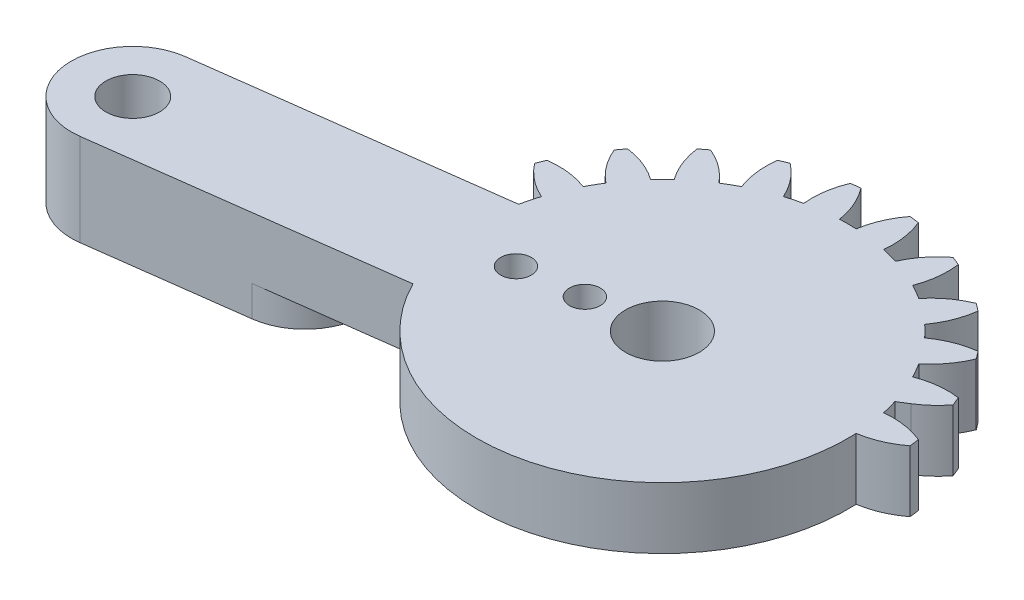
SolidWorks part; units mm, degrees
ref_plane "Front Plane" through (0, 0, 0) normal (0, 0, 1) x (1, 0, 0)
ref_plane "Top Plane" through (0, 0, 0) normal (0, 1, 0) x (1, 0, 0)
ref_plane "Right Plane" through (0, 0, 0) normal (1, 0, 0) x (0, 0, -1)
sketch "Sketch1" plane through (0, 0, 0) normal (0, 1, 0) x (1, 0, 0)
  line L0 (20.6437, 4) -> (2.0816, 4)
  line L1 (2.0816, -4) -> (20.6437, -4)
  arc A0 (2.0816, 4) -> (3.5217, 5.3071) centre (-0.7683, 8.5867) ccw
  arc A1 (3.5217, 5.3071) -> (3.2829, 5.8838) centre (-10.1063, 0) ccw
  arc A2 (3.2829, 5.8838) -> (0.6271, 5.5703) centre (2.5684, 0.5313) ccw
  arc A3 (0.6271, 5.5703) -> (0.0844, 6.5103) centre (-10.1063, 0) ccw
  arc A4 (0.0844, 6.5103) -> (1.6838, 8.6535) centre (-3.3089, 10.711) ccw
  arc A5 (1.6838, 8.6535) -> (1.3038, 9.1487) centre (-10.1063, 0) ccw
  arc A6 (1.3038, 9.1487) -> (-1.1803, 8.1585) centre (1.999, 3.7936) ccw
  arc A7 (-1.1803, 8.1585) -> (-1.9479, 8.926) centre (-10.1063, 0) ccw
  arc A8 (-1.9479, 8.926) -> (-0.9576, 11.4102) centre (-6.3127, 12.1053) ccw
  arc A9 (-0.9576, 11.4102) -> (-1.4528, 11.7901) centre (-10.1063, 0) ccw
  arc A10 (-1.4528, 11.7901) -> (-3.596, 10.1907) centre (0.6046, 6.7975) ccw
  arc A11 (-3.596, 10.1907) -> (-4.5361, 10.7334) centre (-10.1063, 0) ccw
  arc A12 (-4.5361, 10.7334) -> (-4.2225, 13.3892) centre (-9.5751, 12.6747) ccw
  arc A13 (-4.2225, 13.3892) -> (-4.7992, 13.6281) centre (-10.1063, 0) ccw
  arc A14 (-4.7992, 13.6281) -> (-6.4554, 11.5285) centre (-1.5196, 9.3381) ccw
  arc A15 (-6.4554, 11.5285) -> (-7.5039, 11.8094) centre (-10.1063, 0) ccw
  arc A16 (-7.5039, 11.8094) -> (-7.8884, 14.4558) centre (-12.8736, 12.3803) ccw
  arc A17 (-7.8884, 14.4558) -> (-8.5072, 14.5373) centre (-10.1063, 0) ccw
  arc A18 (-8.5072, 14.5373) -> (-9.5636, 12.0806) centre (-4.2291, 11.2423) ccw
  arc A19 (-9.5636, 12.0806) -> (-10.6491, 12.0806) centre (-10.1063, 0) ccw
  arc A20 (-10.6491, 12.0806) -> (-11.7054, 14.5373) centre (-15.9836, 11.2423) ccw
  arc A21 (-11.7054, 14.5373) -> (-12.3243, 14.4558) centre (-10.1063, 0) ccw
  arc A22 (-12.3243, 14.4558) -> (-12.7088, 11.8094) centre (-7.3391, 12.3803) ccw
  arc A23 (-12.7088, 11.8094) -> (-13.7573, 11.5285) centre (-10.1063, 0) ccw
  arc A24 (-13.7573, 11.5285) -> (-15.4135, 13.6281) centre (-18.6931, 9.3381) ccw
  arc A25 (-15.4135, 13.6281) -> (-15.9901, 13.3892) centre (-10.1063, 0) ccw
  arc A26 (-15.9901, 13.3892) -> (-15.6766, 10.7334) centre (-10.6376, 12.6747) ccw
  arc A27 (-15.6766, 10.7334) -> (-16.6166, 10.1907) centre (-10.1063, 0) ccw
  arc A28 (-16.6166, 10.1907) -> (-18.7599, 11.7901) centre (-20.8173, 6.7975) ccw
  arc A29 (-18.7599, 11.7901) -> (-19.255, 11.4102) centre (-10.1063, 0) ccw
  arc A30 (-19.255, 11.4102) -> (-18.2648, 8.926) centre (-13.9, 12.1053) ccw
  arc A31 (-18.2648, 8.926) -> (-19.0324, 8.1585) centre (-10.1063, 0) ccw
  arc A32 (-19.0324, 8.1585) -> (-21.5165, 9.1487) centre (-22.2117, 3.7936) ccw
  arc A33 (-21.5165, 9.1487) -> (-21.8965, 8.6535) centre (-10.1063, 0) ccw
  arc A34 (-21.8965, 8.6535) -> (-20.2971, 6.5103) centre (-16.9038, 10.711) ccw
  arc A35 (-20.2971, 6.5103) -> (-20.8398, 5.5703) centre (-10.1063, 0) ccw
  arc A36 (-20.8398, 5.5703) -> (-23.4956, 5.8838) centre (-22.7811, 0.5313) ccw
  arc A37 (-23.4956, 5.8838) -> (-23.7344, 5.3071) centre (-10.1063, 0) ccw
  arc A38 (-23.7344, 5.3071) -> (-21.6348, 3.6509) centre (-19.4444, 8.5867) ccw
  arc A39 (-21.6348, 3.6509) -> (-21.9157, 2.6025) centre (-10.1063, 0) ccw
  arc A40 (-21.9157, 2.6025) -> (-24.5622, 2.2179) centre (-22.4867, -2.7673) ccw
  arc A41 (-24.5622, 2.2179) -> (-24.6437, 1.5991) centre (-10.1063, 0) ccw
  arc A42 (-24.6437, 1.5991) -> (-22.1869, 0.5427) centre (-21.3486, 5.8773) ccw
  arc A43 (-22.1869, 0.5427) -> (-22.1869, -0.5427) centre (-10.1063, 0) ccw
  arc A44 (-22.1869, -0.5427) -> (-24.6437, -1.5991) centre (-21.3486, -5.8773) ccw
  arc A45 (-24.6437, -1.5991) -> (-24.5622, -2.2179) centre (-10.1063, 0) ccw
  arc A46 (-24.5622, -2.2179) -> (-21.9157, -2.6025) centre (-22.4867, 2.7673) ccw
  arc A47 (-21.9157, -2.6025) -> (-21.6348, -3.6509) centre (-10.1063, 0) ccw
  arc A48 (-21.6348, -3.6509) -> (-23.7344, -5.3071) centre (-19.4444, -8.5867) ccw
  arc A49 (-23.7344, -5.3071) -> (-23.4956, -5.8838) centre (-10.1063, 0) ccw
  arc A50 (-23.4956, -5.8838) -> (-20.8398, -5.5703) centre (-22.7811, -0.5313) ccw
  arc A51 (-20.8398, -5.5703) -> (-20.2971, -6.5103) centre (-10.1063, 0) ccw
  arc A52 (-20.2971, -6.5103) -> (-21.8965, -8.6535) centre (-16.9038, -10.711) ccw
  arc A53 (-21.8965, -8.6535) -> (-21.5165, -9.1487) centre (-10.1063, 0) ccw
  arc A54 (-21.5165, -9.1487) -> (-19.0324, -8.1585) centre (-22.2117, -3.7936) ccw
  arc A55 (-19.0324, -8.1585) -> (-18.2648, -8.926) centre (-10.1063, 0) ccw
  arc A56 (-18.2648, -8.926) -> (-19.255, -11.4102) centre (-13.9, -12.1053) ccw
  arc A57 (-19.255, -11.4102) -> (-18.7599, -11.7901) centre (-10.1063, 0) ccw
  arc A58 (-18.7599, -11.7901) -> (-16.6166, -10.1907) centre (-20.8173, -6.7975) ccw
  arc A59 (-16.6166, -10.1907) -> (-15.6766, -10.7334) centre (-10.1063, 0) ccw
  arc A60 (-15.6766, -10.7334) -> (-15.9901, -13.3892) centre (-10.6376, -12.6747) ccw
  arc A61 (-15.9901, -13.3892) -> (-15.4135, -13.6281) centre (-10.1063, 0) ccw
  arc A62 (-15.4135, -13.6281) -> (-13.7573, -11.5285) centre (-18.6931, -9.3381) ccw
  arc A63 (-13.7573, -11.5285) -> (-12.7088, -11.8094) centre (-10.1063, 0) ccw
  arc A64 (-12.7088, -11.8094) -> (-12.3243, -14.4558) centre (-7.3391, -12.3803) ccw
  arc A65 (-12.3243, -14.4558) -> (-11.7054, -14.5373) centre (-10.1063, 0) ccw
  arc A66 (-11.7054, -14.5373) -> (-10.6491, -12.0806) centre (-15.9836, -11.2423) ccw
  arc A67 (-10.6491, -12.0806) -> (-9.5636, -12.0806) centre (-10.1063, 0) ccw
  arc A68 (-9.5636, -12.0806) -> (-8.5072, -14.5373) centre (-4.2291, -11.2423) ccw
  arc A69 (-8.5072, -14.5373) -> (-7.8884, -14.4558) centre (-10.1063, 0) ccw
  arc A70 (-7.8884, -14.4558) -> (-7.5039, -11.8094) centre (-12.8736, -12.3803) ccw
  arc A71 (-7.5039, -11.8094) -> (-6.4554, -11.5285) centre (-10.1063, 0) ccw
  arc A72 (-6.4554, -11.5285) -> (-4.7992, -13.6281) centre (-1.5196, -9.3381) ccw
  arc A73 (-4.7992, -13.6281) -> (-4.2225, -13.3892) centre (-10.1063, 0) ccw
  arc A74 (-4.2225, -13.3892) -> (-4.5361, -10.7334) centre (-9.5751, -12.6747) ccw
  arc A75 (-4.5361, -10.7334) -> (-3.596, -10.1907) centre (-10.1063, 0) ccw
  arc A76 (-3.596, -10.1907) -> (-1.4528, -11.7901) centre (0.6046, -6.7975) ccw
  arc A77 (-1.4528, -11.7901) -> (-0.9576, -11.4102) centre (-10.1063, 0) ccw
  arc A78 (-0.9576, -11.4102) -> (-1.9479, -8.926) centre (-6.3127, -12.1053) ccw
  arc A79 (-1.9479, -8.926) -> (-1.1803, -8.1585) centre (-10.1063, 0) ccw
  arc A80 (-1.1803, -8.1585) -> (1.3038, -9.1487) centre (1.999, -3.7936) ccw
  arc A81 (1.3038, -9.1487) -> (1.6838, -8.6535) centre (-10.1063, 0) ccw
  arc A82 (1.6838, -8.6535) -> (0.0844, -6.5103) centre (-3.3089, -10.711) ccw
  arc A83 (0.0844, -6.5103) -> (0.6271, -5.5703) centre (-10.1063, 0) ccw
  arc A84 (0.6271, -5.5703) -> (3.2829, -5.8838) centre (2.5684, -0.5313) ccw
  arc A85 (3.2829, -5.8838) -> (3.5217, -5.3071) centre (-10.1063, 0) ccw
  arc A86 (3.5217, -5.3071) -> (2.0816, -4) centre (-0.7683, -8.5867) ccw
  arc A87 (20.6437, -4) -> (20.6437, 4) centre (20.6437, 0) ccw
  circle A88 centre (-10.1063, 0) radius 1.5
  circle A89 centre (20.6437, 0) radius 1.5
  dimension "D1" = 3
  dimension "D2" = 3
extrude "Boss-Extrude1" add sketch "Sketch1" along normal blind 4
sketch "Sketch3" plane through (0, 4, 0) normal (0, 1, 0) x (1, 0, 0)
  line L0 (-10.1063, 0) -> (-40.8563, 0) construction
  line L1 (-10.1063, 0) -> (-40.5933, -4.0137)
  line L2 (-10.6284, 3.9658) -> (-41.1154, -0.0479)
  line L3 (-9.5842, -3.9658) -> (-40.0712, -7.9795)
  line L4 (-10.1063, 0) -> (-4.5096, 13.5117) construction
  line L5 (-10.1063, 0) -> (-8.1974, 14.4999) construction
  circle A0 centre (-10.1063, 0) radius 1.5
  circle A1 centre (20.6437, 0) radius 1.5 construction
  circle A2 centre (20.6437, 0) radius 1.5
  circle A3 centre (-40.5933, -4.0137) radius 1.75
  circle A4 centre (-40.5933, -4.0137) radius 4
  circle A5 centre (-10.1063, 0) radius 4
  arc A6 (-4.2225, 13.3892) -> (-4.7992, 13.6281) centre (-10.1063, 0) ccw construction
  arc A7 (-7.8884, 14.4558) -> (-8.5072, 14.5373) centre (-10.1063, 0) ccw construction
  dimension "D2" = 3
  dimension "D5" = 3.5
  dimension "D6" = 8
  dimension "D7" = 8
  dimension "D1" = 30.75
  dimension "D4" = 7.5
extrude "Boss-Extrude2" add sketch "Sketch3" against normal blind 4
sketch "Sketch4" plane through (0, 4, 0) normal (0, 1, 0) x (1, 0, 0)
  line L0 (20.6437, 4) -> (2.0816, 4) construction
  line L1 (2.0816, -4) -> (20.6437, -4) construction
  line L2 (20.6437, 4) -> (2.0816, 4)
  line L3 (2.0816, -4) -> (20.6437, -4)
  line L4 (2.0816, 4) -> (1.4381, 3.6001)
  line L5 (-21.6245, -5.5509) -> (-20.8986, -5.4553)
  line L6 (-10.1063, 0) -> (0.0844, 6.5103) construction
  line L7 (-10.1063, 0) -> (1.9742, 0.5427) construction
  line L8 (-24.5755, 2.1296) -> (-41.1154, -0.0479)
  line L9 (-40.0712, -7.9795) -> (-23.5312, -5.8019)
  line L10 (2.0816, -4) -> (20.6437, -4)
  line L11 (20.6437, 4) -> (2.0816, 4)
  line L12 (-21.9429, 2.4762) -> (-41.1154, -0.0479)
  line L13 (-40.0712, -7.9795) -> (-21.6245, -5.5509)
  line L14 (2.0816, -4) -> (20.6437, -4)
  line L15 (20.6437, 4) -> (2.0816, 4)
  circle A0 centre (-10.1063, 0) radius 12.0927
  arc A1 (3.2829, 5.8838) -> (0.6271, 5.5703) centre (2.5684, 0.5313) ccw construction
  arc A2 (3.5217, 5.3071) -> (3.2829, 5.8838) centre (-10.1063, 0) ccw construction
  arc A3 (2.0816, 4) -> (3.5217, 5.3071) centre (-0.7683, 8.5867) ccw construction
  arc A4 (20.6437, -4) -> (20.6437, 4) centre (20.6437, 0) ccw construction
  arc A5 (3.5217, -5.3071) -> (2.0816, -4) centre (-0.7683, -8.5867) ccw construction
  arc A6 (3.2829, -5.8838) -> (3.5217, -5.3071) centre (-10.1063, 0) ccw construction
  arc A7 (0.6271, -5.5703) -> (3.2829, -5.8838) centre (2.5684, -0.5313) ccw construction
  arc A8 (3.2829, 5.8838) -> (0.6271, 5.5703) centre (2.5684, 0.5313) ccw
  arc A9 (3.5217, 5.3071) -> (3.2829, 5.8838) centre (-10.1063, 0) ccw
  arc A10 (2.0816, 4) -> (3.5217, 5.3071) centre (-0.7683, 8.5867) ccw
  arc A11 (20.6437, -4) -> (20.6437, 4) centre (20.6437, 0) ccw
  arc A12 (3.5217, -5.3071) -> (2.0816, -4) centre (-0.7683, -8.5867) ccw
  arc A13 (3.2829, -5.8838) -> (3.5217, -5.3071) centre (-10.1063, 0) ccw
  arc A14 (0.6271, -5.5703) -> (3.2829, -5.8838) centre (2.5684, -0.5313) ccw
  arc A15 (1.9742, 0.5427) -> (4.431, 1.5991) centre (1.1359, 5.8773) ccw
  arc A16 (4.3495, 2.2179) -> (1.7031, 2.6025) centre (2.274, -2.7673) ccw
  arc A17 (4.431, 1.5991) -> (4.3495, 2.2179) centre (-10.1063, 0) ccw
  arc A95 (-21.6348, 3.6509) -> (-21.9157, 2.6025) centre (-10.1063, 0) ccw
  arc A96 (-41.1154, -0.0479) -> (-40.0712, -7.9795) centre (-40.5933, -4.0137) ccw
  arc A97 (-20.2971, -6.5103) -> (-21.8965, -8.6535) centre (-16.9038, -10.711) ccw
  arc A98 (-21.8965, -8.6535) -> (-21.5165, -9.1487) centre (-10.1063, 0) ccw
  arc A99 (-21.5165, -9.1487) -> (-19.0324, -8.1585) centre (-22.2117, -3.7936) ccw
  arc A100 (-19.0324, -8.1585) -> (-18.2648, -8.926) centre (-10.1063, 0) ccw
  arc A101 (-18.2648, -8.926) -> (-19.255, -11.4102) centre (-13.9, -12.1053) ccw
  arc A102 (-19.255, -11.4102) -> (-18.7599, -11.7901) centre (-10.1063, 0) ccw
  arc A103 (-18.7599, -11.7901) -> (-16.6166, -10.1907) centre (-20.8173, -6.7975) ccw
  arc A104 (-16.6166, -10.1907) -> (-15.6766, -10.7334) centre (-10.1063, 0) ccw
  arc A105 (-15.6766, -10.7334) -> (-15.9901, -13.3892) centre (-10.6376, -12.6747) ccw
  arc A106 (-15.9901, -13.3892) -> (-15.4135, -13.6281) centre (-10.1063, 0) ccw
  arc A107 (-15.4135, -13.6281) -> (-13.7573, -11.5285) centre (-18.6931, -9.3381) ccw
  arc A108 (-13.7573, -11.5285) -> (-12.7088, -11.8094) centre (-10.1063, 0) ccw
  arc A109 (-12.7088, -11.8094) -> (-12.3243, -14.4558) centre (-7.3391, -12.3803) ccw
  arc A110 (-12.3243, -14.4558) -> (-11.7054, -14.5373) centre (-10.1063, 0) ccw
  arc A111 (-11.7054, -14.5373) -> (-10.6491, -12.0806) centre (-15.9836, -11.2423) ccw
  arc A112 (-10.6491, -12.0806) -> (-9.5636, -12.0806) centre (-10.1063, 0) ccw
  arc A113 (-9.5636, -12.0806) -> (-8.5072, -14.5373) centre (-4.2291, -11.2423) ccw
  arc A114 (-8.5072, -14.5373) -> (-7.8884, -14.4558) centre (-10.1063, 0) ccw
  arc A115 (-7.8884, -14.4558) -> (-7.5039, -11.8094) centre (-12.8736, -12.3803) ccw
  arc A116 (-7.5039, -11.8094) -> (-6.4554, -11.5285) centre (-10.1063, 0) ccw
  arc A117 (-6.4554, -11.5285) -> (-4.7992, -13.6281) centre (-1.5196, -9.3381) ccw
  arc A118 (-4.7992, -13.6281) -> (-4.2225, -13.3892) centre (-10.1063, 0) ccw
  arc A119 (-4.2225, -13.3892) -> (-4.5361, -10.7334) centre (-9.5751, -12.6747) ccw
  arc A120 (-4.5361, -10.7334) -> (-3.596, -10.1907) centre (-10.1063, 0) ccw
  arc A121 (-3.596, -10.1907) -> (-1.4528, -11.7901) centre (0.6046, -6.7975) ccw
  arc A122 (-1.4528, -11.7901) -> (-0.9576, -11.4102) centre (-10.1063, 0) ccw
  arc A123 (-0.9576, -11.4102) -> (-1.9479, -8.926) centre (-6.3127, -12.1053) ccw
  arc A124 (-1.9479, -8.926) -> (-1.1803, -8.1585) centre (-10.1063, 0) ccw
  arc A125 (-1.1803, -8.1585) -> (1.3038, -9.1487) centre (1.999, -3.7936) ccw
  arc A126 (1.3038, -9.1487) -> (1.6838, -8.6535) centre (-10.1063, 0) ccw
  arc A127 (1.6838, -8.6535) -> (0.0844, -6.5103) centre (-3.3089, -10.711) ccw
  arc A128 (0.0844, -6.5103) -> (0.6271, -5.5703) centre (-10.1063, 0) ccw
  arc A129 (0.6271, -5.5703) -> (3.2829, -5.8838) centre (2.5684, -0.5313) ccw
  arc A130 (3.2829, -5.8838) -> (3.5217, -5.3071) centre (-10.1063, 0) ccw
  arc A131 (3.5217, -5.3071) -> (2.0816, -4) centre (-0.7683, -8.5867) ccw
  arc A132 (20.6437, -4) -> (20.6437, 4) centre (20.6437, 0) ccw
  arc A133 (2.0816, 4) -> (3.5217, 5.3071) centre (-0.7683, 8.5867) ccw
  arc A134 (3.5217, 5.3071) -> (3.2829, 5.8838) centre (-10.1063, 0) ccw
  arc A135 (3.2829, 5.8838) -> (0.6271, 5.5703) centre (2.5684, 0.5313) ccw
  arc A136 (0.6271, 5.5703) -> (0.0844, 6.5103) centre (-10.1063, 0) ccw
  arc A137 (0.0844, 6.5103) -> (1.6838, 8.6535) centre (-3.3089, 10.711) ccw
  arc A138 (1.6838, 8.6535) -> (1.3038, 9.1487) centre (-10.1063, 0) ccw
  arc A139 (1.3038, 9.1487) -> (-1.1803, 8.1585) centre (1.999, 3.7936) ccw
  arc A140 (-1.1803, 8.1585) -> (-1.9479, 8.926) centre (-10.1063, 0) ccw
  arc A141 (-1.9479, 8.926) -> (-0.9576, 11.4102) centre (-6.3127, 12.1053) ccw
  arc A142 (-0.9576, 11.4102) -> (-1.4528, 11.7901) centre (-10.1063, 0) ccw
  arc A143 (-1.4528, 11.7901) -> (-3.596, 10.1907) centre (0.6046, 6.7975) ccw
  arc A144 (-3.596, 10.1907) -> (-4.5361, 10.7334) centre (-10.1063, 0) ccw
  arc A145 (-4.5361, 10.7334) -> (-4.2225, 13.3892) centre (-9.5751, 12.6747) ccw
  arc A146 (-4.2225, 13.3892) -> (-4.7992, 13.6281) centre (-10.1063, 0) ccw
  arc A147 (-4.7992, 13.6281) -> (-6.4554, 11.5285) centre (-1.5196, 9.3381) ccw
  arc A148 (-6.4554, 11.5285) -> (-7.5039, 11.8094) centre (-10.1063, 0) ccw
  arc A149 (-7.5039, 11.8094) -> (-7.8884, 14.4558) centre (-12.8736, 12.3803) ccw
  arc A150 (-7.8884, 14.4558) -> (-8.5072, 14.5373) centre (-10.1063, 0) ccw
  arc A151 (-8.5072, 14.5373) -> (-9.5636, 12.0806) centre (-4.2291, 11.2423) ccw
  arc A152 (-9.5636, 12.0806) -> (-10.6491, 12.0806) centre (-10.1063, 0) ccw
  arc A153 (-10.6491, 12.0806) -> (-11.7054, 14.5373) centre (-15.9836, 11.2423) ccw
  arc A154 (-11.7054, 14.5373) -> (-12.3243, 14.4558) centre (-10.1063, 0) ccw
  arc A155 (-12.3243, 14.4558) -> (-12.7088, 11.8094) centre (-7.3391, 12.3803) ccw
  arc A156 (-12.7088, 11.8094) -> (-13.7573, 11.5285) centre (-10.1063, 0) ccw
  arc A157 (-13.7573, 11.5285) -> (-15.4135, 13.6281) centre (-18.6931, 9.3381) ccw
  arc A158 (-15.4135, 13.6281) -> (-15.9901, 13.3892) centre (-10.1063, 0) ccw
  arc A159 (-15.9901, 13.3892) -> (-15.6766, 10.7334) centre (-10.6376, 12.6747) ccw
  arc A160 (-15.6766, 10.7334) -> (-16.6166, 10.1907) centre (-10.1063, 0) ccw
  arc A161 (-16.6166, 10.1907) -> (-18.7599, 11.7901) centre (-20.8173, 6.7975) ccw
  arc A162 (-18.7599, 11.7901) -> (-19.255, 11.4102) centre (-10.1063, 0) ccw
  arc A163 (-19.255, 11.4102) -> (-18.2648, 8.926) centre (-13.9, 12.1053) ccw
  arc A164 (-18.2648, 8.926) -> (-19.0324, 8.1585) centre (-10.1063, 0) ccw
  arc A165 (-19.0324, 8.1585) -> (-21.5165, 9.1487) centre (-22.2117, 3.7936) ccw
  arc A166 (-21.5165, 9.1487) -> (-21.8965, 8.6535) centre (-10.1063, 0) ccw
  arc A167 (-21.8965, 8.6535) -> (-20.2971, 6.5103) centre (-16.9038, 10.711) ccw
  arc A168 (-20.2971, 6.5103) -> (-20.8398, 5.5703) centre (-10.1063, 0) ccw
  arc A169 (-20.8398, 5.5703) -> (-23.4956, 5.8838) centre (-22.7811, 0.5313) ccw
  arc A170 (-23.4956, 5.8838) -> (-23.7344, 5.3071) centre (-10.1063, 0) ccw
  arc A171 (-23.7344, 5.3071) -> (-21.6348, 3.6509) centre (-19.4444, 8.5867) ccw
  arc A172 (-21.6348, 3.6509) -> (-21.9157, 2.6025) centre (-10.1063, 0) ccw
  arc A175 (-23.4956, -5.8838) -> (-20.8398, -5.5703) centre (-22.7811, -0.5313) ccw
  arc A176 (-41.1154, -0.0479) -> (-40.0712, -7.9795) centre (-40.5933, -4.0137) ccw
  arc A177 (-20.2971, -6.5103) -> (-21.8965, -8.6535) centre (-16.9038, -10.711) ccw
  arc A178 (-21.8965, -8.6535) -> (-21.5165, -9.1487) centre (-10.1063, 0) ccw
  arc A179 (-21.5165, -9.1487) -> (-19.0324, -8.1585) centre (-22.2117, -3.7936) ccw
  arc A180 (-19.0324, -8.1585) -> (-18.2648, -8.926) centre (-10.1063, 0) ccw
  arc A181 (-18.2648, -8.926) -> (-19.255, -11.4102) centre (-13.9, -12.1053) ccw
  arc A182 (-19.255, -11.4102) -> (-18.7599, -11.7901) centre (-10.1063, 0) ccw
  arc A183 (-18.7599, -11.7901) -> (-16.6166, -10.1907) centre (-20.8173, -6.7975) ccw
  arc A184 (-16.6166, -10.1907) -> (-15.6766, -10.7334) centre (-10.1063, 0) ccw
  arc A185 (-15.6766, -10.7334) -> (-15.9901, -13.3892) centre (-10.6376, -12.6747) ccw
  arc A186 (-15.9901, -13.3892) -> (-15.4135, -13.6281) centre (-10.1063, 0) ccw
  arc A187 (-15.4135, -13.6281) -> (-13.7573, -11.5285) centre (-18.6931, -9.3381) ccw
  arc A188 (-13.7573, -11.5285) -> (-12.7088, -11.8094) centre (-10.1063, 0) ccw
  arc A189 (-12.7088, -11.8094) -> (-12.3243, -14.4558) centre (-7.3391, -12.3803) ccw
  arc A190 (-12.3243, -14.4558) -> (-11.7054, -14.5373) centre (-10.1063, 0) ccw
  arc A191 (-11.7054, -14.5373) -> (-10.6491, -12.0806) centre (-15.9836, -11.2423) ccw
  arc A192 (-10.6491, -12.0806) -> (-9.5636, -12.0806) centre (-10.1063, 0) ccw
  arc A193 (-9.5636, -12.0806) -> (-8.5072, -14.5373) centre (-4.2291, -11.2423) ccw
  arc A194 (-8.5072, -14.5373) -> (-7.8884, -14.4558) centre (-10.1063, 0) ccw
  arc A195 (-7.8884, -14.4558) -> (-7.5039, -11.8094) centre (-12.8736, -12.3803) ccw
  arc A196 (-7.5039, -11.8094) -> (-6.4554, -11.5285) centre (-10.1063, 0) ccw
  arc A197 (-6.4554, -11.5285) -> (-4.7992, -13.6281) centre (-1.5196, -9.3381) ccw
  arc A198 (-4.7992, -13.6281) -> (-4.2225, -13.3892) centre (-10.1063, 0) ccw
  arc A199 (-4.2225, -13.3892) -> (-4.5361, -10.7334) centre (-9.5751, -12.6747) ccw
  arc A200 (-4.5361, -10.7334) -> (-3.596, -10.1907) centre (-10.1063, 0) ccw
  arc A201 (-3.596, -10.1907) -> (-1.4528, -11.7901) centre (0.6046, -6.7975) ccw
  arc A202 (-1.4528, -11.7901) -> (-0.9576, -11.4102) centre (-10.1063, 0) ccw
  arc A203 (-0.9576, -11.4102) -> (-1.9479, -8.926) centre (-6.3127, -12.1053) ccw
  arc A204 (-1.9479, -8.926) -> (-1.1803, -8.1585) centre (-10.1063, 0) ccw
  arc A205 (-1.1803, -8.1585) -> (1.3038, -9.1487) centre (1.999, -3.7936) ccw
  arc A206 (1.3038, -9.1487) -> (1.6838, -8.6535) centre (-10.1063, 0) ccw
  arc A207 (1.6838, -8.6535) -> (0.0844, -6.5103) centre (-3.3089, -10.711) ccw
  arc A208 (0.0844, -6.5103) -> (0.6271, -5.5703) centre (-10.1063, 0) ccw
  arc A209 (0.6271, -5.5703) -> (3.2829, -5.8838) centre (2.5684, -0.5313) ccw
  arc A210 (3.2829, -5.8838) -> (3.5217, -5.3071) centre (-10.1063, 0) ccw
  arc A211 (3.5217, -5.3071) -> (2.0816, -4) centre (-0.7683, -8.5867) ccw
  arc A212 (20.6437, -4) -> (20.6437, 4) centre (20.6437, 0) ccw
  arc A213 (2.0816, 4) -> (3.5217, 5.3071) centre (-0.7683, 8.5867) ccw
  arc A214 (3.5217, 5.3071) -> (3.2829, 5.8838) centre (-10.1063, 0) ccw
  arc A215 (3.2829, 5.8838) -> (0.6271, 5.5703) centre (2.5684, 0.5313) ccw
  arc A216 (0.6271, 5.5703) -> (0.0844, 6.5103) centre (-10.1063, 0) ccw
  arc A217 (0.0844, 6.5103) -> (1.6838, 8.6535) centre (-3.3089, 10.711) ccw
  arc A218 (1.6838, 8.6535) -> (1.3038, 9.1487) centre (-10.1063, 0) ccw
  arc A219 (1.3038, 9.1487) -> (-1.1803, 8.1585) centre (1.999, 3.7936) ccw
  arc A220 (-1.1803, 8.1585) -> (-1.9479, 8.926) centre (-10.1063, 0) ccw
  arc A221 (-1.9479, 8.926) -> (-0.9576, 11.4102) centre (-6.3127, 12.1053) ccw
  arc A222 (-0.9576, 11.4102) -> (-1.4528, 11.7901) centre (-10.1063, 0) ccw
  arc A223 (-1.4528, 11.7901) -> (-3.596, 10.1907) centre (0.6046, 6.7975) ccw
  arc A224 (-3.596, 10.1907) -> (-4.5361, 10.7334) centre (-10.1063, 0) ccw
  arc A225 (-4.5361, 10.7334) -> (-4.2225, 13.3892) centre (-9.5751, 12.6747) ccw
  arc A226 (-4.2225, 13.3892) -> (-4.7992, 13.6281) centre (-10.1063, 0) ccw
  arc A227 (-4.7992, 13.6281) -> (-6.4554, 11.5285) centre (-1.5196, 9.3381) ccw
  arc A228 (-6.4554, 11.5285) -> (-7.5039, 11.8094) centre (-10.1063, 0) ccw
  arc A229 (-7.5039, 11.8094) -> (-7.8884, 14.4558) centre (-12.8736, 12.3803) ccw
  arc A230 (-7.8884, 14.4558) -> (-8.5072, 14.5373) centre (-10.1063, 0) ccw
  arc A231 (-8.5072, 14.5373) -> (-9.5636, 12.0806) centre (-4.2291, 11.2423) ccw
  arc A232 (-9.5636, 12.0806) -> (-10.6491, 12.0806) centre (-10.1063, 0) ccw
  arc A233 (-10.6491, 12.0806) -> (-11.7054, 14.5373) centre (-15.9836, 11.2423) ccw
  arc A234 (-11.7054, 14.5373) -> (-12.3243, 14.4558) centre (-10.1063, 0) ccw
  arc A235 (-12.3243, 14.4558) -> (-12.7088, 11.8094) centre (-7.3391, 12.3803) ccw
  arc A236 (-12.7088, 11.8094) -> (-13.7573, 11.5285) centre (-10.1063, 0) ccw
  arc A237 (-13.7573, 11.5285) -> (-15.4135, 13.6281) centre (-18.6931, 9.3381) ccw
  arc A238 (-15.4135, 13.6281) -> (-15.9901, 13.3892) centre (-10.1063, 0) ccw
  arc A239 (-15.9901, 13.3892) -> (-15.6766, 10.7334) centre (-10.6376, 12.6747) ccw
  arc A240 (-15.6766, 10.7334) -> (-16.6166, 10.1907) centre (-10.1063, 0) ccw
  arc A241 (-16.6166, 10.1907) -> (-18.7599, 11.7901) centre (-20.8173, 6.7975) ccw
  arc A242 (-18.7599, 11.7901) -> (-19.255, 11.4102) centre (-10.1063, 0) ccw
  arc A243 (-19.255, 11.4102) -> (-18.2648, 8.926) centre (-13.9, 12.1053) ccw
  arc A244 (-18.2648, 8.926) -> (-19.0324, 8.1585) centre (-10.1063, 0) ccw
  arc A245 (-19.0324, 8.1585) -> (-21.5165, 9.1487) centre (-22.2117, 3.7936) ccw
  arc A246 (-21.5165, 9.1487) -> (-21.8965, 8.6535) centre (-10.1063, 0) ccw
  arc A247 (-21.8965, 8.6535) -> (-20.2971, 6.5103) centre (-16.9038, 10.711) ccw
  arc A248 (-20.2971, 6.5103) -> (-20.8398, 5.5703) centre (-10.1063, 0) ccw
  arc A249 (-20.8398, 5.5703) -> (-23.4956, 5.8838) centre (-22.7811, 0.5313) ccw
  arc A250 (-23.4956, 5.8838) -> (-23.7344, 5.3071) centre (-10.1063, 0) ccw
  arc A251 (-23.7344, 5.3071) -> (-21.6348, 3.6509) centre (-19.4444, 8.5867) ccw
  arc A252 (-23.4956, -5.8838) -> (-20.8398, -5.5703) centre (-22.7811, -0.5313) ccw
  arc A253 (-20.8398, -5.5703) -> (-20.2971, -6.5103) centre (-10.1063, 0) ccw
  arc A254 (-20.8398, -5.5703) -> (-20.2971, -6.5103) centre (-10.1063, 0) ccw
  arc A255 (-23.5312, -5.8019) -> (-23.4956, -5.8838) centre (-10.1063, 0) ccw
  arc A256 (-23.5312, -5.8019) -> (-23.4956, -5.8838) centre (-10.1063, 0) ccw
  arc A257 (-21.9157, 2.6025) -> (-24.5622, 2.2179) centre (-22.4867, -2.7673) ccw
  arc A258 (-21.9157, 2.6025) -> (-24.5622, 2.2179) centre (-22.4867, -2.7673) ccw
  arc A259 (-24.5622, 2.2179) -> (-24.5755, 2.1296) centre (-10.1063, 0) ccw
  arc A260 (-24.5622, 2.2179) -> (-24.5755, 2.1296) centre (-10.1063, 0) ccw
  point P40 (-10.1063, 0)
  dimension "D2" = 24.1855
  dimension "D4" = 30
  dimension "D1" = 0
  dimension "D3" = 2
extrude "Cut-Extrude1" cut sketch "Sketch4" against normal blind 4 contours A178 A179 A0 L5 A177 | A182 A183 A0 A181 | A186 A187 A0 A185 | A190 A191 A0 A189 | A194 A195 A0 A193 | A198 A199 A0 A197 | A202 A203 A0 A201 | A206 A207 A0 A205 | A258 A260 L12 A0 | L13 A256 A252 A0 L5 | A0 A14 A13 A12 L3 A11 L2 L4
sketch "Sketch5" plane through (0, 4, 0) normal (0, 1, 0) x (1, 0, 0)
  line L0 (-10.1063, 0) -> (-40.5933, -4.0137) construction
  circle A0 centre (-10.1063, 0) radius 2.4
  circle A2 centre (-14.5678, -0.5874) radius 1
  circle A4 centre (-18.5336, -1.1095) radius 1
  dimension "D1" = 4.8
  dimension "D2" = 4.5
  dimension "D3" = 2
  dimension "D4" = 2
  dimension "D5" = 4
extrude "Cut-Extrude2" cut sketch "Sketch5" against normal up to next
sketch "Sketch7" plane through (0, 4, 0) normal (0, 1, 0) x (1, 0, 0)
  circle A0 centre (-10.1063, 0) radius 13.3199 construction
  circle A1 centre (-10.1063, 0) radius 13.3199
sketch "Sketch8" plane through (0, 0, 0) normal (0, -1, 0) x (1, 0, 0)
  line L0 (-30.6788, 2.7084) -> (-40.5933, 4.0137) construction
  line L1 (-20.8986, 5.4553) -> (-40.0712, 7.9795) construction
  line L2 (-30.1567, 6.6742) -> (-40.0712, 7.9795)
  line L3 (-21.9429, -2.4762) -> (-41.1154, 0.0479) construction
  line L4 (-31.2009, -1.2574) -> (-41.1154, 0.0479)
  arc A0 (-31.2009, -1.2574) -> (-30.1567, 6.6742) centre (-30.6788, 2.7084) ccw
  arc A1 (-40.0712, 7.9795) -> (-41.1154, 0.0479) centre (-40.5933, 4.0137) ccw construction
  arc A2 (-40.0712, 7.9795) -> (-41.1154, 0.0479) centre (-40.5933, 4.0137) ccw
  circle A3 centre (-40.5933, 4.0137) radius 1.75 construction
  circle A4 centre (-40.5933, 4.0137) radius 1.75
  dimension "D1" = 10
extrude "Boss-Extrude3" add sketch "Sketch8" along normal blind 2
